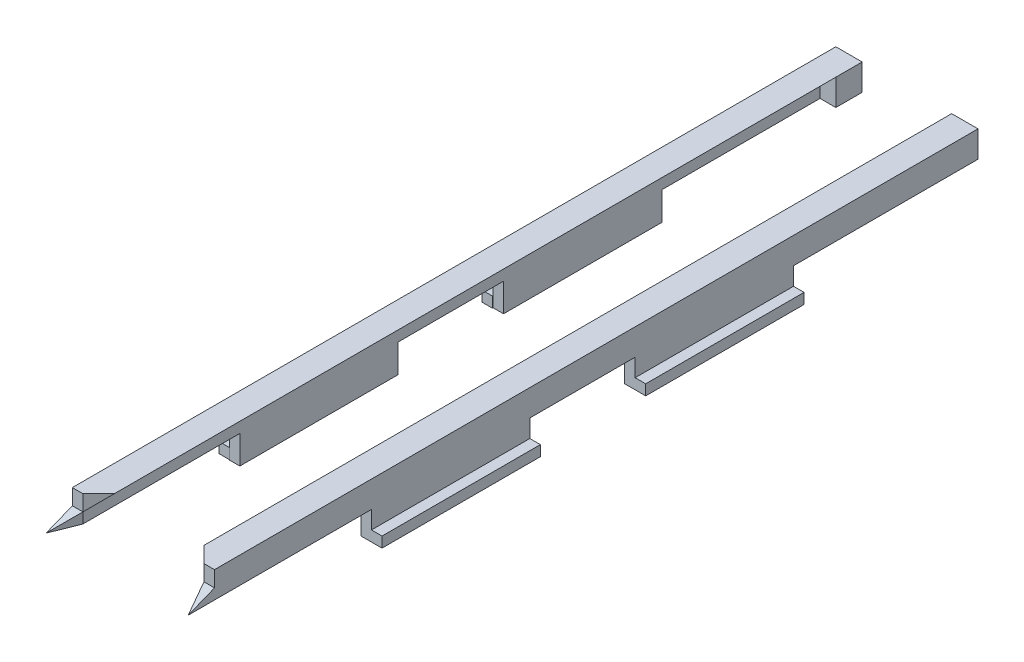
SolidWorks part; units mm, degrees
material "ABS"
ref_plane "Front Plane" through (0, 0, 0) normal (0, 0, 1) x (1, 0, 0)
ref_plane "Top Plane" through (0, 0, 0) normal (0, 1, 0) x (1, 0, 0)
ref_plane "Right Plane" through (0, 0, 0) normal (1, 0, 0) x (0, 0, -1)
sketch "Sketch2" plane through (0, 0, 0) normal (0, 0, 1) x (1, 0, 0)
  line L1 (-11.5, 2) -> (-8.5, 5)
  line L2 (-13.5, 0) -> (-13.5, 5)
  line L4 (-13.5, 5) -> (-8.5, 5)
  line L7 (0, 0) -> (0, 10.0778) construction
  line L8 (-13.5, 0) -> (-11.5, 0)
  line L9 (-11.5, 0) -> (-11.5, 2)
  line L10 (11.5, 0) -> (11.5, 2)
  line L11 (13.5, 0) -> (11.5, 0)
  line L12 (13.5, 5) -> (8.5, 5)
  line L13 (13.5, 0) -> (13.5, 5)
  line L14 (11.5, 2) -> (8.5, 5)
  point P4 (0, 0)
extrude "Boss-Extrude1" add sketch "Sketch2" along normal blind 145
sketch "Sketch4" plane through (0, 5, 0) normal (0, 1, 0) x (1, 0, 0)
  line L0 (-8.5, -145) -> (-8.5, -142)
  line L1 (-8.5, -145) -> (-8.5, 0) construction
  line L2 (-8.5, -142) -> (-11.5, -145)
  line L3 (-8.5, -145) -> (-13.5, -145) construction
  line L4 (-11.5, -145) -> (-8.5, -145)
extrude "Cut-Extrude1" cut sketch "Sketch4" against normal blind 3
sketch "Sketch5" plane through (-11.5, 0, 0) normal (1, 0, 0) x (0, 0, -1)
  line L0 (-145, 0) -> (-150, 0)
  line L1 (-150, 0) -> (-145, 2)
  line L2 (-145, 2) -> (-145, 0)
extrude "Boss-Extrude2" add sketch "Sketch5" against normal blind 2
sketch "Sketch6" plane through (0, 0, 0) normal (0, -1, 0) x (1, 0, 0)
  line L0 (-13.5, 150) -> (-11.5, 150)
  line L1 (-11.5, 150) -> (-11.5, 145)
  line L2 (-11.5, 150) -> (-11.5, 0) construction
  line L3 (-11.5, 145) -> (-13.5, 150)
extrude "Cut-Extrude2" cut sketch "Sketch6" against normal blind 2
sketch "Sketch7" plane through (0, 0, 0) normal (0, 0, -1) x (-1, 0, 0)
  line L0 (8.5, 5) -> (11.5, 2)
  line L1 (11.5, 2) -> (11.5, 0)
  line L2 (11.5, 0) -> (8.5, 0)
  line L3 (8.5, 0) -> (8.5, 5)
extrude "Boss-Extrude3" add sketch "Sketch7" against normal blind 5
sketch "Sketch8" plane through (0, 5, 0) normal (0, 1, 0) x (1, 0, 0)
  line L0 (8.5, -145) -> (8.5, -142)
  line L1 (8.5, -145) -> (8.5, 0) construction
  line L2 (8.5, -142) -> (11.5, -145)
  line L3 (13.5, -145) -> (8.5, -145) construction
  line L4 (11.5, -145) -> (8.5, -145)
extrude "Cut-Extrude3" cut sketch "Sketch8" against normal blind 3
sketch "Sketch9" plane through (0, 0, 0) normal (0, -1, 0) x (1, 0, 0)
  line L0 (13.5, 145) -> (13.5, 150)
  line L1 (13.5, 150) -> (11.5, 145)
  line L2 (11.5, 145) -> (13.5, 145)
extrude "Boss-Extrude4" add sketch "Sketch9" against normal blind 2
sketch "Sketch10" plane through (13.5, 0, 0) normal (1, 0, 0) x (0, 0, -1)
  line L0 (-150, 2) -> (-145, 2)
  line L1 (-145, 2) -> (-150, 0)
  line L2 (-150, 0) -> (-150, 2)
extrude "Cut-Extrude4" cut sketch "Sketch10" against normal blind 2
sketch "Sketch11" plane through (0, 0, 0) normal (0, 0, -1) x (-1, 0, 0)
  line L0 (-8.5, 5) -> (-8.5, 0)
  line L1 (-8.5, 0) -> (-11.5, 0)
  line L2 (-11.5, 0) -> (-11.5, 2)
  line L3 (-11.5, 2) -> (-8.5, 5)
extrude "Boss-Extrude5" add sketch "Sketch11" against normal blind 5
sketch "Sketch12" plane through (-13.5, 0, 0) normal (1, 0, 0) x (0, 0, -1)
  line L0 (-35.0292, 0) -> (-35.0292, -5.3717)
  line L1 (-150, 0) -> (0, 0) construction
  line L2 (-65.1093, 0) -> (-35.0292, 0)
  line L3 (-65.1093, 0) -> (-65.1093, -5.3717)
  line L4 (-115.1895, 0) -> (-115.1895, -5.3717)
  line L5 (-115.1895, 0) -> (-85.1093, 0)
  line L6 (-115.1895, -5.3717) -> (-85.1093, -5.3717)
  line L7 (-85.1093, 0) -> (-85.1093, -5.3717)
  line L8 (-65.1093, -5.3717) -> (-35.0292, -5.3717)
extrude "Boss-Extrude6" add sketch "Sketch12" along normal blind 2
sketch "Sketch13" plane through (-13.5, 0, 0) normal (1, 0, 0) x (0, 0, -1)
  line L0 (-85.1093, -3.3717) -> (-85.1093, -5.3717)
  line L3 (-85.1093, -3.3717) -> (-115.125, -3.3717)
  line L4 (-85.1093, -5.3717) -> (-115.125, -5.3717)
  line L5 (-115.125, -3.3717) -> (-115.125, -5.3717)
  line L6 (-85.1093, -5.3717) -> (-85.1093, 0) construction
  arc A2 (-85.1093, -13.3717) -> (-85.1093, -3.3717) centre (-85.1093, -8.3717) ccw construction
extrude "Boss-Extrude7" add sketch "Sketch13" against normal blind 2
sketch "Sketch15" plane through (13.5, 0, 0) normal (-1, 0, 0) x (0, 0, 1)
  line L0 (85.1093, -3.3717) -> (115.1895, -3.3717)
  line L1 (85.1093, -3.3717) -> (115.1895, -3.3717)
  line L2 (85.1093, -3.3717) -> (85.1093, 0)
  line L3 (115.1895, -3.3717) -> (115.1895, 0)
  line L4 (85.1093, 0) -> (115.1895, 0)
  line L5 (85.1093, -3.3717) -> (85.1093, -5.3717)
  line L6 (115.1895, -3.3717) -> (115.1895, -5.3717)
  line L7 (85.1093, -5.3717) -> (115.1895, -5.3717)
  line L8 (35.0292, 0) -> (65.1093, 0)
  line L9 (35.0292, -3.3717) -> (35.0292, 0)
  line L10 (65.1093, -3.3717) -> (65.1093, 0)
  line L11 (35.0292, -3.3717) -> (65.1093, -3.3717)
  line L12 (35.0292, -3.3717) -> (35.0292, -5.3717)
  line L13 (65.1093, -3.3717) -> (65.1093, -5.3717)
  line L14 (35.0292, -3.3717) -> (65.1093, -3.3717)
  line L15 (35.0292, -5.3717) -> (65.1093, -5.3717)
  line M6 (85.1093, -3.3717) -> (115.1895, -3.3717)
  line M10 (35.0292, -3.3717) -> (65.1093, -3.3717)
extrude "Boss-Extrude10" add sketch "Sketch15" along normal blind 2 contours L4 L2 L3 M6 | L5 L7 L6 M6 | L10 L8 L9 M10 | L12 L15 L13 M10
sketch "Sketch16" plane through (13.5, 0, 0) normal (1, 0, 0) x (0, 0, -1)
  line L0 (-115.1895, -5.3717) -> (-85.1093, -5.3717)
  line L1 (-115.1895, -5.3717) -> (-115.1895, -3.379)
  line L2 (-85.1093, -5.3717) -> (-85.1093, -3.379)
  line L3 (-115.1895, -3.379) -> (-85.1093, -3.379)
  line L4 (-35.0292, -5.3717) -> (-35.0292, -3.379)
  line L5 (-65.1093, -3.379) -> (-35.0292, -3.379)
  line L6 (-65.1093, -5.3717) -> (-65.1093, -3.379)
  line L7 (-65.1093, -5.3717) -> (-35.0292, -5.3717)
extrude "Boss-Extrude11" add sketch "Sketch16" along normal blind 2
sketch "Sketch17" plane through (-13.5, 0, 0) normal (-1, 0, 0) x (0, 0, 1)
  line L0 (35.0292, -3.3717) -> (35.0292, -5.3717)
  line L1 (35.0292, -3.3717) -> (65.2433, -3.3717)
  line L2 (35.0292, -5.3717) -> (65.2433, -5.3717)
  line L3 (65.2433, -3.3717) -> (65.2433, -5.3717)
  line L4 (35.0292, -5.3717) -> (35.0292, 0) construction
  arc A0 (35.0292, -3.3717) -> (35.0292, -13.3717) centre (35.0292, -8.3717) ccw construction
extrude "Boss-Extrude12" add sketch "Sketch17" along normal blind 2
